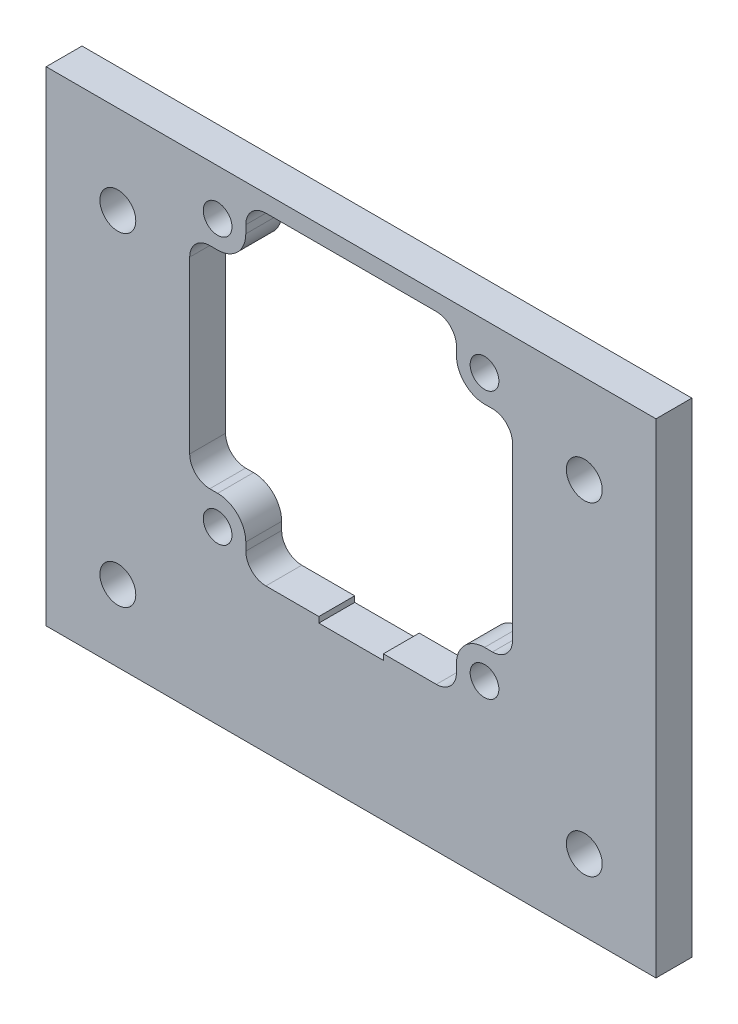
SolidWorks part; units mm, degrees
ref_plane "Front Plane" through (0, 0, 0) normal (0, 0, 1) x (1, 0, 0)
ref_plane "Top Plane" through (0, 0, 0) normal (0, 1, 0) x (1, 0, 0)
ref_plane "Right Plane" through (0, 0, 0) normal (1, 0, 0) x (0, 0, -1)
sketch "Sketch1" plane through (0, 0, 0) normal (0, 0, 1) x (1, 0, 0)
  line L0 (-2.667, -1.7227) -> (-2.667, 1.7227) construction
  line L1 (28.575, -28.575) -> (-28.575, -28.575) construction
  line L2 (28.575, -28.575) -> (28.575, 28.575) construction
  line L3 (28.575, 28.575) -> (-28.575, 28.575) construction
  line L4 (-28.575, -28.575) -> (-28.575, 28.575) construction
  line L5 (28.575, -28.575) -> (-28.575, 28.575) construction
  line L6 (28.575, 28.575) -> (-28.575, -28.575) construction
  line L7 (23.622, -23.622) -> (-23.622, -23.622) construction
  line L8 (23.622, -23.622) -> (23.622, 23.622) construction
  line L9 (23.622, 23.622) -> (-23.622, 23.622) construction
  line L10 (-23.622, -23.622) -> (-23.622, 23.622) construction
  line L11 (23.622, -23.622) -> (-23.622, 23.622) construction
  line L12 (23.622, 23.622) -> (-23.622, -23.622) construction
  line L14 (53.975, 31.75) -> (-53.975, 31.75)
  line L15 (53.975, 31.75) -> (53.975, 0)
  line L16 (53.975, 0) -> (-53.975, 0)
  line L17 (-53.975, 31.75) -> (-53.975, 0)
  line L18 (0, 0) -> (0, 31.75) construction
  line L19 (53.975, 15.875) -> (-53.975, 15.875) construction
  line L20 (53.975, -53.975) -> (-53.975, -53.975)
  line L21 (53.975, -53.975) -> (53.975, 0)
  line L22 (53.975, 0) -> (-53.975, 0)
  line L23 (-53.975, -53.975) -> (-53.975, 0)
  line L24 (0, 0) -> (0, -53.975) construction
  line L25 (53.975, -26.9875) -> (-53.975, -26.9875) construction
  circle A0 centre (-23.622, 23.622) radius 2.54 construction
  circle A1 centre (23.622, 23.622) radius 2.54 construction
  circle A2 centre (-23.622, -23.622) radius 2.54 construction
  circle A3 centre (23.622, -23.622) radius 2.54 construction
  point P0 (0, 0)
  point P6 (0, 0)
  point P15 (0, 0)
  point P16 (0, 15.875)
  point P18 (0, 3.175)
  point P19 (0, 28.575)
  point P20 (0, 19.05)
  point P21 (-23.622, -26.162)
  point P27 (0, -26.9875)
  dimension "D3" = 5.08
  dimension "D4" = 107.95
  dimension "D5" = 53.975
  dimension "D1" = 107.95
  dimension "Width" = 57.15
  dimension "D2" = 31.75
  dimension "CenterToCenter" = 47.244
sketch "Sketch3" plane through (0, 0, 0) normal (0, 0, 1) x (1, 0, 0)
  line L1 (-28.575, -28.575) -> (-28.575, 28.575) construction
  line L2 (28.575, 28.575) -> (-28.575, 28.575) construction
  line L3 (28.575, -28.575) -> (28.575, 28.575) construction
  line L4 (28.575, -28.575) -> (-28.575, -28.575) construction
  line L5 (-28.575, -25.4) -> (-28.575, 25.4)
  line L6 (25.4, 28.575) -> (-25.4, 28.575)
  line L7 (28.575, -25.4) -> (28.575, 25.4)
  line L8 (25.4, -28.575) -> (-25.4, -28.575)
  arc A4 (-28.575, 25.4) -> (-25.4, 28.575) centre (-25.4, 25.4) cw
  arc A5 (25.4, 28.575) -> (28.575, 25.4) centre (25.4, 25.4) cw
  arc A6 (28.575, -25.4) -> (25.4, -28.575) centre (25.4, -25.4) cw
  arc A7 (-25.4, -28.575) -> (-28.575, -25.4) centre (-25.4, -25.4) cw
  dimension "D1" = 3.175
extrude "Boss-Extrude1" add sketch "Sketch1" along normal blind 6.35 contours L14 L17 L16 L15 | L23 L20 L21 L16
sketch "Sketch11" plane through (0, 0, 0) normal (0, 0, -1) x (-1, 0, 0)
  line L4 (-23.622, 23.622) -> (-23.622, -23.622)
  line L5 (-23.622, -23.622) -> (23.622, -23.622)
  line L6 (-23.622, 23.622) -> (23.622, 23.622)
  line L7 (23.622, 23.622) -> (23.622, -23.622)
  circle A0 centre (23.622, -23.622) radius 2.54
  circle A1 centre (-23.622, -23.622) radius 2.54
  circle A2 centre (-23.622, 23.622) radius 2.54
  circle A3 centre (23.622, 23.622) radius 2.54
  dimension "D1" = 47.244
  dimension "D2" = 47.244
extrude "Cut-Extrude2" cut sketch "Sketch11" against normal blind 7.62 contours A2 | A3 | A0 | A1
sketch "Sketch12" plane through (0, 0, 0) normal (0, 0, -1) x (-1, 0, 0)
  line L0 (-0.0085, 28.7524) -> (-0.0085, 0.1774) construction
  line L1 (-0.0085, 0.1774) -> (-28.5835, 0.1774) construction
  line L2 (-25.0275, 18.821) -> (-23.6305, 18.821)
  line L3 (-18.6521, 23.7994) -> (-18.6521, 25.1964)
  line L4 (-28.5835, 15.265) -> (-28.5835, -14.9102)
  line L5 (15.0791, 28.7524) -> (-15.0961, 28.7524)
  line L6 (28.5665, -14.9102) -> (28.5665, 15.265)
  line L7 (18.6351, 23.7994) -> (18.6351, 25.1964)
  line L8 (25.0105, 18.821) -> (23.6135, 18.821)
  line L9 (25.0105, -18.4662) -> (23.6135, -18.4662)
  line L10 (18.6351, -23.4446) -> (18.6351, -24.8416)
  line L11 (15.0791, -28.3976) -> (-15.0961, -28.3976)
  line L12 (-18.6521, -23.4446) -> (-18.6521, -24.8416)
  line L13 (-25.0275, -18.4662) -> (-23.6305, -18.4662)
  line L15 (-5.7235, -29.4136) -> (5.7065, -29.4136)
  line L16 (-5.7235, -29.4136) -> (-5.7235, -28.3976)
  line L17 (-5.7235, -28.3976) -> (5.7065, -28.3976)
  line L18 (5.7065, -29.4136) -> (5.7065, -28.3976)
  arc A0 (-25.0275, 18.821) -> (-28.5835, 15.265) centre (-25.0275, 15.265) ccw
  arc A1 (-15.0961, 28.7524) -> (-18.6521, 25.1964) centre (-15.0961, 25.1964) ccw
  arc A2 (-23.6305, 18.821) -> (-18.6521, 23.7994) centre (-23.6305, 23.7994) ccw
  arc A3 (23.6135, 18.821) -> (18.6351, 23.7994) centre (23.6135, 23.7994) cw
  arc A4 (15.0791, 28.7524) -> (18.6351, 25.1964) centre (15.0791, 25.1964) cw
  arc A5 (25.0105, 18.821) -> (28.5665, 15.265) centre (25.0105, 15.265) cw
  arc A6 (25.0105, -18.4662) -> (28.5665, -14.9102) centre (25.0105, -14.9102) ccw
  arc A7 (15.0791, -28.3976) -> (18.6351, -24.8416) centre (15.0791, -24.8416) ccw
  arc A8 (23.6135, -18.4662) -> (18.6351, -23.4446) centre (23.6135, -23.4446) ccw
  arc A9 (-23.6305, -18.4662) -> (-18.6521, -23.4446) centre (-23.6305, -23.4446) cw
  arc A10 (-15.0961, -28.3976) -> (-18.6521, -24.8416) centre (-15.0961, -24.8416) cw
  arc A11 (-25.0275, -18.4662) -> (-28.5835, -14.9102) centre (-25.0275, -14.9102) cw
  point P43 (-0.0085, -28.3976)
  point P44 (-0.0085, -28.3976)
  dimension "D3" = 1.016
  dimension "D4" = 11.43
extrude "Cut-Extrude3" cut sketch "Sketch12" against normal blind 7.62 contours A11 L13 A9 L12 A10 L11 A7 L10 A8 L9 A6 L6 A5 L8 A3 L7 A4 L5 A1 L3 A2 L2 A0 L4 | L15 L18 L11 L16
sketch "Sketch13" plane through (0, 0, 0) normal (0, 0, -1) x (-1, 0, 0)
  line L0 (-41.2835, 31.75) -> (-41.2835, -53.975) construction
  line L1 (-53.975, 31.75) -> (53.975, 31.75) construction
  line L2 (-53.975, -53.975) -> (53.975, -53.975) construction
  line L3 (-28.5835, 15.265) -> (-28.5835, -14.9102) construction
  line L4 (15.0791, 28.7524) -> (-15.0961, 28.7524) construction
  line L5 (0, 31.75) -> (0, -53.975) construction
  circle A0 centre (-41.2835, 16.0524) radius 3.175
  circle A1 centre (-41.2835, -41.275) radius 3.175
  circle A2 centre (41.2835, -41.275) radius 3.175
  circle A3 centre (41.2835, 16.0524) radius 3.175
  dimension "D1" = 6.35
  dimension "D2" = 12.7
  dimension "D3" = 12.7
  dimension "D4" = 12.7
extrude "Cut-Extrude4" cut sketch "Sketch13" against normal blind 7.62 contours A0 | A1 | A2 | A3
